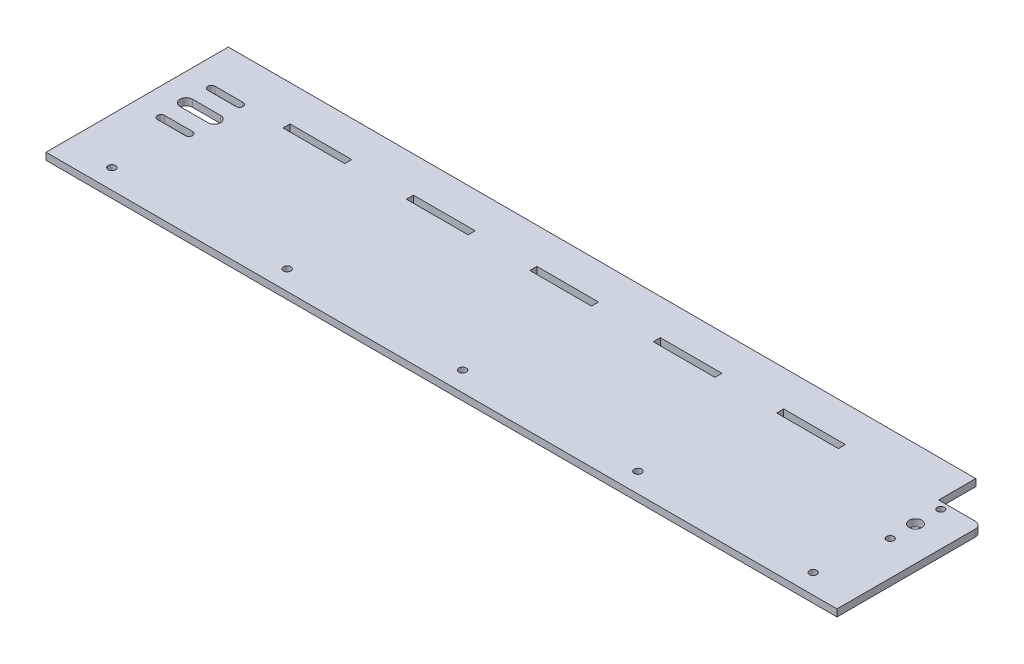
SolidWorks part; units mm, degrees
ref_plane "Front Plane" through (0, 0, 0) normal (0, 0, 1) x (1, 0, 0)
ref_plane "Top Plane" through (0, 0, 0) normal (0, 1, 0) x (1, 0, 0)
ref_plane "Right Plane" through (0, 0, 0) normal (1, 0, 0) x (0, 0, -1)
sketch "Sketch1" plane through (0, 0, 0) normal (0, 1, 0) x (1, 0, 0)
  line L0 (0, 0) -> (0, 33.5)
  line L2 (-450.5105, 34.5) -> (-494.5105, 34.5)
  line L4 (-494.5105, 34.5) -> (-494.5105, 39.5)
  line L5 (0, 0) -> (0, -65)
  line L6 (0, -65) -> (-524.5, -65)
  line L7 (-524.5, -65) -> (-564, -65)
  line L8 (-31, 38.5) -> (-31, 65)
  line L9 (-494.5105, 39.5) -> (-450.5105, 39.5)
  line L10 (-406.5105, 34.5) -> (-362.5105, 34.5)
  line L11 (-406.5105, 39.5) -> (-362.5105, 39.5)
  line L12 (-31, 38.5) -> (-5, 38.5)
  line L13 (-544.5, 36.05) -> (-524.5, 36.05)
  line L14 (-544.5, 30.95) -> (-524.5, 30.95)
  line L15 (-524.5, 0.05) -> (-544.5, 0.05)
  line L16 (-524.5, -5.05) -> (-544.5, -5.05)
  line L17 (-318.5105, 34.5) -> (-274.5105, 34.5)
  line L18 (-544.5, 20) -> (-524.5, 20)
  line L19 (-544.5, 11) -> (-524.5, 11)
  line L20 (-564, -65) -> (-564, 65)
  line L21 (-274.5105, 39.5) -> (-318.5105, 39.5)
  line L22 (-31, 65) -> (-564, 65)
  line L23 (-230.5105, 34.5) -> (-186.5105, 34.5)
  line L24 (-564, -65) -> (-531, -65)
  line L25 (-230.5105, 39.5) -> (-186.5105, 39.5)
  line L29 (-98.5105, 34.5) -> (-98.5105, 39.5)
  line L31 (-142.5105, 39.5) -> (-142.5105, 34.5)
  line L33 (-186.5105, 34.5) -> (-186.5105, 39.5)
  line L35 (-230.5105, 39.5) -> (-230.5105, 34.5)
  line L36 (-98.5105, 34.5) -> (-142.5105, 34.5)
  line L37 (-274.5105, 34.5) -> (-274.5105, 39.5)
  line L38 (-142.5105, 39.5) -> (-98.5105, 39.5)
  line L39 (-318.5105, 39.5) -> (-318.5105, 34.5)
  line L41 (-362.5105, 34.5) -> (-362.5105, 39.5)
  line L43 (-406.5105, 39.5) -> (-406.5105, 34.5)
  line L45 (-450.5105, 34.5) -> (-450.5105, 39.5)
  arc A0 (0, 33.5) -> (-5, 38.5) centre (-5, 33.5) ccw
  circle A1 centre (-24.5, 33.5) radius 2.55
  circle A2 centre (-24.5, -2.5) radius 2.55
  circle A3 centre (-24.5, 15.5) radius 4.5
  arc A4 (-524.5, 30.95) -> (-524.5, 36.05) centre (-524.5, 33.5) ccw
  arc A6 (-524.5, -5.05) -> (-524.5, 0.05) centre (-524.5, -2.5) ccw
  arc A7 (-524.5, 11) -> (-524.5, 20) centre (-524.5, 15.5) ccw
  arc A8 (-544.5, 36.05) -> (-544.5, 30.95) centre (-544.5, 33.5) ccw
  arc A9 (-544.5, 20) -> (-544.5, 11) centre (-544.5, 15.5) ccw
  arc A10 (-544.5, 0.05) -> (-544.5, -5.05) centre (-544.5, -2.5) ccw
  circle A11 centre (-531, -51) radius 2.65
  circle A12 centre (-406, -51) radius 2.65
  circle A13 centre (-281, -51) radius 2.65
  circle A14 centre (-156, -51) radius 2.65
  circle A15 centre (-31, -51) radius 2.65
  dimension "D4" = 18
  dimension "D6" = 9
  dimension "D8" = 5.1
  dimension "D9" = 5.1
  dimension "D12" = 31
  dimension "D13" = 65
  dimension "D19" = 5.1
  dimension "D20" = 5.1
  dimension "D21" = 9
  dimension "D24" = 5.1
  dimension "D25" = 20
  dimension "D26" = 9
  dimension "D30" = 125
  dimension "D7" = 5
  dimension "D11" = 5.3
  dimension "D5" = 18
  dimension "D10" = 44
  dimension "D15" = 524.5
  dimension "D16" = 39.5
  dimension "D17" = 18
  dimension "D18" = 18
  dimension "D22" = 20
  dimension "D23" = 20
  dimension "D27" = 33
  dimension "D28" = 14
  dimension "D29" = 125
  dimension "D31" = 125
  dimension "D32" = 125
  dimension "D34" = 44
  dimension "D35" = 44
  dimension "D36" = 44
  dimension "D37" = 44
  dimension "D39" = 44
  dimension "D40" = 44
  dimension "D41" = 44
  dimension "D42" = 44
extrude "Boss-Extrude1" add sketch "Sketch1" along normal blind 5 contours L0 A0 L12 L8 L22 L20 L7 L6 L5 A15 A14 A13 A12 A11 A10 L15 A6 L16 A9 L18 A7 L19 A8 L13 A4 L14 A3 A2 A1 L31 L38 L29 L36 L35 L25 L33 L23
